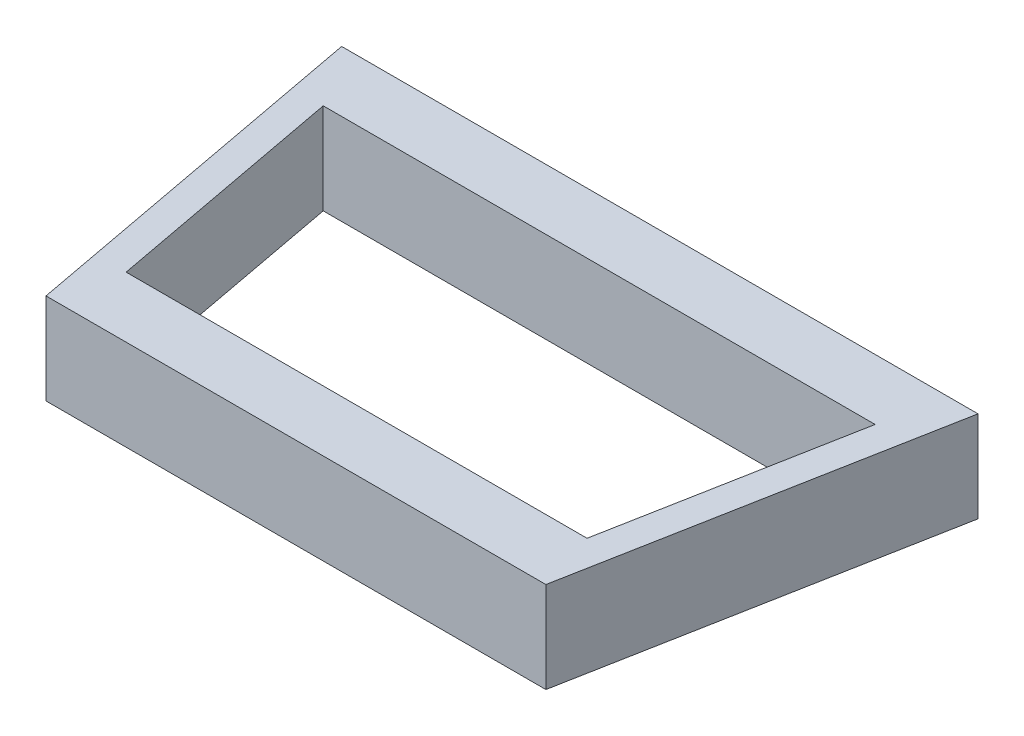
SolidWorks part; units mm, degrees
ref_plane "Front Plane" through (0, 0, 0) normal (0, 0, 1) x (1, 0, 0)
ref_plane "Top Plane" through (0, 0, 0) normal (0, 1, 0) x (1, 0, 0)
ref_plane "Right Plane" through (0, 0, 0) normal (1, 0, 0) x (0, 0, -1)
sketch "Sketch1" plane through (0, 0, 0) normal (0, 1, 0) x (1, 0, 0)
  line L0 (-9.1, 4) -> (9.1, 4)
  line L1 (9.1, 4) -> (7.6, -4)
  line L2 (7.6, -4) -> (-7.6, -4)
  line L3 (-7.6, -4) -> (-9.1, 4)
  line L4 (0, 0) -> (0, 4) construction
  line L5 (-10.4924, 6) -> (10.4924, 6)
  line L6 (10.4924, 6) -> (8.2424, -6)
  line L7 (8.2424, -6) -> (-8.2424, -6)
  line L8 (-8.2424, -6) -> (-10.4924, 6)
  dimension "D1" = 18.2
  dimension "D2" = 15.2
  dimension "D3" = 4
  dimension "D4" = 4
  dimension "D6" = 2
  dimension "D5" = 1
  dimension "D7" = 2
  dimension "D8" = 1
extrude "Boss-Extrude1" add sketch "Sketch1" along normal blind 10
sketch "Sketch2" plane through (0, 10, 0) normal (0, 1, 0) x (1, 0, 0)
  line L4 (-10.4924, 6) -> (-8.2424, -6)
  line L5 (-8.2424, -6) -> (8.2424, -6)
  line L6 (8.2424, -6) -> (10.4924, 6)
  line L7 (10.4924, 6) -> (-10.4924, 6)
  line L8 (-10.4924, 6) -> (-8.2424, -6)
  line L9 (-8.2424, -6) -> (8.2424, -6)
  line L10 (8.2424, -6) -> (10.4924, 6)
  line L11 (10.4924, 6) -> (-10.4924, 6)
  dimension "D1" = 0
extrude "Boss-Extrude2" add sketch "Sketch2" along normal blind 1
sketch "Sketch3" plane through (0, 11, 0) normal (0, 1, 0) x (1, 0, 0)
  line L0 (0, 0) -> (0, -9) construction
  line L1 (10.4924, 6) -> (-10.4924, 6) construction
  line L2 (-5, 6) -> (5, 6)
  line L3 (-5, 6) -> (-5, 9)
  line L4 (-5, 9) -> (5, 9)
  line L5 (5, 6) -> (5, 9)
  line L6 (-8.2424, -6) -> (8.2424, -6) construction
  line L7 (-5, -6) -> (5, -6)
  line L8 (-5, -6) -> (-5, -9)
  line L9 (-5, -9) -> (5, -9)
  line L10 (5, -6) -> (5, -9)
  line L11 (0, 0) -> (0, 9) construction
  point P0 (0, 0)
  dimension "D1" = 10
  dimension "D2" = 3
extrude "Boss-Extrude3" add sketch "Sketch3" against normal blind 3
fillet "Fillet1" radius 1 16 edges at (-5, 9.5, 9) (-5, 8, 7.5) (5, 8, 7.5) (5, 9.5, 9) (5, 9.5, -9) (5, 8, -7.5) (-5, 8, -7.5) (-5, 9.5, -9) (0, 8, -9) (0, 8, 9) (0, 8, 6) (0, 8, -6)
ref_plane "Plane1" through (0, 3, 0) normal (0, -1, 0) x (-1, 0, 0)
split "Split1" trim tools "Plane1" bodies to split 103 resulting bodies 105
